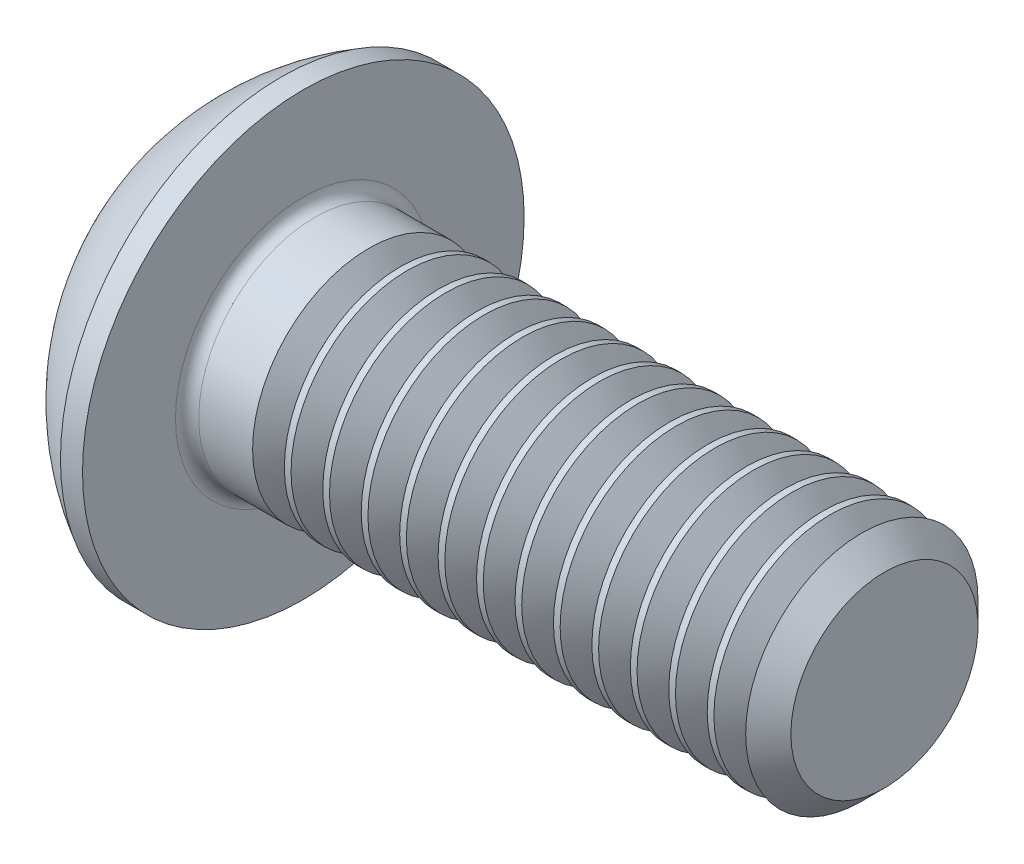
SolidWorks part; units mm, degrees
ref_plane "Plane1" through (0, 0, 0) normal (0, 0, 1) x (1, 0, 0)
ref_plane "Plane2" through (0, 0, 0) normal (0, 1, 0) x (1, 0, 0)
ref_plane "Plane3" through (0, 0, 0) normal (1, 0, 0) x (0, 0, -1)
sketch "BodySke" plane through (0, 0, 0) normal (0, 0, 1) x (1, 0, 0)
  line L0 (12.2, 0) -> (12.2, 1.61)
  line L1 (11.81, 2) -> (2.2, 2)
  line L2 (2.2, 2) -> (2.2, 3.8)
  line L3 (2.2, 3.8) -> (1.82, 3.8)
  line L4 (0, 0) -> (101.6, 0) construction
  line L5 (2.2, -3.8) -> (1.82, -3.8) construction
  line L6 (55.6768, -2) -> (2.2, -2) construction
  line L7 (12.2, 0) -> (0, 0)
  line L8 (0, 1.9) -> (0, -1.9) construction
  line L9 (0, 0) -> (0, 1.9)
  line L10 (12.2, 1.61) -> (11.81, 2)
  line L11 (12.2, -1.61) -> (11.81, -2) construction
  line L12 (2.9, 9.525) -> (2.9, -2) construction
  line L13 (2.2, 9.525) -> (2.2, -2) construction
  arc A1 (0, 1.9) -> (1.82, 3.8) centre (3.8853, 0) cw
  dimension "Diameter" = 4
  dimension "Length" = 10
  dimension "Head_dia" = 7.6
  dimension "D1" = 3.8
  dimension "Head_ht" = 2.2
  dimension "Head_side_ht" = 0.38
  dimension "Minor_dia" = 3.22
  dimension "Body_ch_ang" = 45
  dimension "Advance" = 0.7
  dimension "Thread_nom" = 10
revolve "BaseBody" add sketch "BodySke" angle 360 about L4
cosmetic thread "ThreadCosmetic" [suppressed] parameters "Thread_length"=8.6, "Thread_minor"=3.22
fillet "Fillet1" radius 0.2 1 edges at (2.2, 0, 2)
sketch "Sketch2" plane through (0, 0, 0) normal (0, 0, 1) x (1, 0, 0)
  line L0 (0, 1.25) -> (1.3, 1.25)
  line L1 (1.3, 1.25) -> (2.0217, 0)
  line L3 (2.0217, 0) -> (0, 0)
  line L4 (0, 0) -> (0, 1.25)
  line L5 (0, -1.25) -> (1.3, -1.25) construction
  line L6 (0, 0) -> (47.625, 0) construction
  dimension "D2" = 60
  dimension "PreBroach_depth" = 1.3
  dimension "PreBroach_dia" = 2.5
revolve "PreBroach" cut sketch "Sketch2" angle 360 about L6
sketch "Sketch3" plane through (0, 0, 0) normal (1, 0, 0) x (0, 0, -1)
  line L0 (-1.25, -0.7217) -> (-1.25, 0.7217)
  line L1 (-1.25, 0.7217) -> (0, 1.4434)
  line L2 (0, 1.4434) -> (1.25, 0.7217)
  line L3 (1.25, 0.7217) -> (1.25, -0.7217)
  line L4 (1.25, -0.7217) -> (0, -1.4434)
  line L5 (0, -1.4434) -> (-1.25, -0.7217)
  dimension "Hex_size" = 2.5
  dimension "D3" = 2.5
  dimension "D1" = 1.25
  dimension "D2" = 1.25
extrude "Hex" cut sketch "Sketch3" along normal blind 1.3
sketch "ThdSchSke" plane through (0, 0, 0) normal (0, 0, 1) x (1, 0, 0)
  line L0 (3.6, -1.61) -> (3.3269, -2)
  line L1 (3.6, -1.61) -> (3.8731, -2)
  line L2 (3.8731, -2) -> (3.8731, -2.5)
  line L3 (-3.175, 0) -> (5.1513, 0) construction
  line L5 (3.8731, -2.5) -> (3.3269, -2.5)
  line L6 (3.3269, -2.5) -> (3.3269, -2)
  dimension "Diameter" = 4
  dimension "Thread_minor" = 3.22
  dimension "SideAngle" = 55
  dimension "VeeAngle" = 70
  dimension "Overcut" = 5
  dimension "Start" = 3.6
revolve "ThreadSchematic" cut sketch "ThdSchSke" angle 360 about L3
pattern_linear "ThdSchPat" count 13 spacing 0.6615 along (1, 0, 0) of "ThreadSchematic"
equation "\"D1@BodySke\" = \"Head_dia@BodySke\" * .5"
equation "\"Thread_minor@ThreadCosmetic\" = \"Minor_dia@BodySke\""
equation "\"D1@Sketch3\" = \"Hex_size@Sketch3\" / 2"
equation "\"D2@Sketch3\" = \"D1@Sketch3\""
equation "\"D3@Sketch3\" = \"Hex_size@Sketch3\""
equation "\"Thread_length@ThreadCosmetic\" = ((sgn( (\"Length@BodySke\" - \"Advance@BodySke\" * 2.0) - \"Thread_nom@BodySke\" )-1)*( (\"Length@BodySke\" - \"Advance@BodySke\" * 2.0) - \"Thread_nom@BodySke\" ))/-2+ \"Thread_nom@BodySke\""
equation "\"Thread_minor@ThdSchSke\" = \"Minor_dia@BodySke\""
equation "\"Diameter@ThdSchSke\" = \"Diameter@BodySke\""
equation "\"Overcut@ThdSchSke\" = \"Diameter@BodySke\" * 1.25"
equation "\"Start@ThdSchSke\" = \"Head_ht@BodySke\" + \"Length@BodySke\" - \"Thread_length@ThreadCosmetic\"  '---Non-countersunk---"
equation "\"Num_threads@ThdSchPat\" = int( \"Thread_length@ThreadCosmetic\" / \"Advance@BodySke\" + 0.999 )  + 1"
equation "\"Advance@ThdSchPat\" = \"Thread_length@ThreadCosmetic\" /  (\"Num_threads@ThdSchPat\" - 1) 'relax it"
equation "\"Num_threads@ThdSchPat\" = \"Num_threads@ThdSchPat\" - sgn( \"Num_threads@ThdSchPat\" - 1) '---chamfered tips only---"
